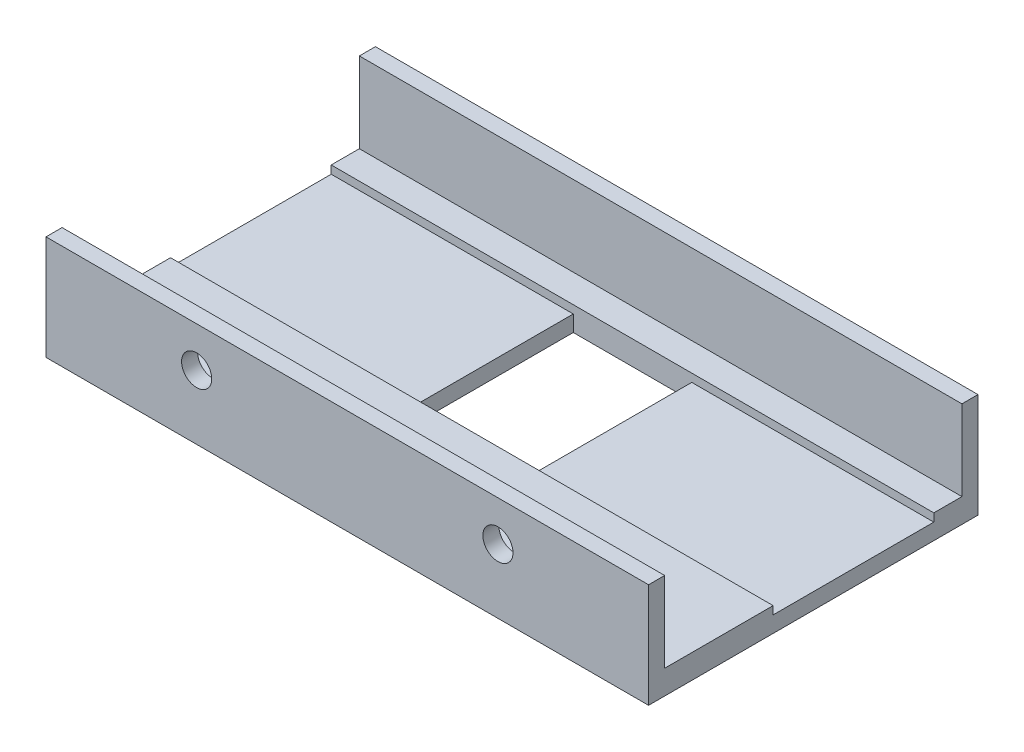
SolidWorks part; units mm, degrees
material "1345 Alloy"
ref_plane "Front Plane" through (0, 0, 0) normal (0, 0, 1) x (1, 0, 0)
ref_plane "Top Plane" through (0, 0, 0) normal (0, 1, 0) x (1, 0, 0)
ref_plane "Right Plane" through (0, 0, 0) normal (1, 0, 0) x (0, 0, -1)
sketch "Sketch1" plane through (0, 0, 0) normal (0, 1, 0) x (1, 0, 0)
  line L1 (-37.5, 20.5) -> (37.5, 20.5)
  line L2 (-37.5, 20.5) -> (-37.5, -20.5)
  line L3 (-37.5, -20.5) -> (37.5, -20.5)
  line L4 (37.5, 20.5) -> (37.5, -20.5)
  line L5 (-37.5, 20.5) -> (37.5, -20.5) construction
  line L6 (-37.5, -20.5) -> (37.5, 20.5) construction
  point P0 (0, 0)
  dimension "D1" = 41
  dimension "D2" = 75
extrude "Boss-Extrude1" add sketch "Sketch1" along normal blind 3
sketch "Sketch2" plane through (0, 3, 0) normal (0, 1, 0) x (1, 0, 0)
  line L0 (37.5, -20.5) -> (37.5, 20.5) construction
  line L1 (-37.5, 20.5) -> (37.5, 20.5)
  line L2 (-37.5, 20.5) -> (-37.5, 18.5)
  line L3 (-37.5, 18.5) -> (37.5, 18.5)
  line L4 (37.5, 20.5) -> (37.5, 18.5)
  dimension "D1" = 2
extrude "Boss-Extrude2" add sketch "Sketch2" along normal blind 10
sketch "Sketch3" plane through (0, 3, 0) normal (0, 1, 0) x (1, 0, 0)
  line L0 (37.5, -20.5) -> (37.5, 18.5) construction
  line L1 (-37.5, -20.5) -> (37.5, -20.5)
  line L2 (-37.5, -20.5) -> (-37.5, -18.5)
  line L3 (-37.5, -18.5) -> (37.5, -18.5)
  line L4 (37.5, -20.5) -> (37.5, -18.5)
  dimension "D1" = 2
extrude "Boss-Extrude3" add sketch "Sketch3" along normal up to surface (10 mm away) up to face at (0, 13, -19.5)
sketch "Sketch4" plane through (0, 0, 20.5) normal (0, 0, 1) x (1, 0, 0)
  line L4 (0, 0) -> (0, 13) construction
  line L5 (-37.5, 0) -> (37.5, 0) construction
  line L6 (-37.5, 13) -> (37.5, 13) construction
  line L8 (-39.5, -2) -> (39.5, -2)
  line L9 (39.5, -2) -> (39.5, 15)
  line L10 (39.5, 15) -> (-39.5, 15)
  line L11 (-39.5, 15) -> (-39.5, -2)
  line L12 (-39.5, -2) -> (39.5, -2)
  line L13 (39.5, -2) -> (39.5, 15)
  line L14 (39.5, 15) -> (-39.5, 15)
  line L15 (-39.5, 15) -> (-39.5, -2)
  circle A1 centre (18.75, 8) radius 1.875
  circle A2 centre (-18.75, 8) radius 1.875
  circle A3 centre (-18.75, 8) radius 1.875
  dimension "D1" = 2
  dimension "D2" = 0.5
extrude "Cut-Extrude2" cut sketch "Sketch4" against normal up to surface (2 mm away) flip side to cut up to face at (0, 8, 18.5)
sketch "Sketch6" plane through (0, 3, 0) normal (0, 1, 0) x (1, 0, 0)
  line L0 (-37.5, 18.5) -> (-37.5, -8.5) construction
  line L1 (-37.5, 18.5) -> (-37.5, -18.5) construction
  line L2 (-37.5, -8.5) -> (37.5, -8.5) construction
  line L3 (37.5, -18.5) -> (37.5, 18.5) construction
  line L4 (37.5, -8.5) -> (37.5, 18.5) construction
  line L5 (37.5, 18.5) -> (-37.5, 18.5) construction
  line L6 (-22.9033, -8.5) -> (22.0967, -8.5) construction
  line L7 (-37.5, 5) -> (37.5, 5) construction
  line L8 (0, 18.5) -> (0, -8.5) construction
  line L10 (-7.375, 15) -> (7.375, 15)
  line L11 (-7.375, 15) -> (-7.375, -5)
  line L12 (-7.375, -5) -> (7.375, -5)
  line L13 (7.375, 15) -> (7.375, -5)
  line L14 (-7.375, 15) -> (7.375, -5) construction
  line L15 (-7.375, -5) -> (7.375, 15) construction
  point P17 (0, 5)
  dimension "D1" = 14.75
  dimension "D2" = 20
  dimension "D3" = 3.5
extrude "Cut-Extrude3" cut sketch "Sketch6" against normal through all
sketch "Sketch7" plane through (0, 3, 0) normal (0, 1, 0) x (1, 0, 0)
  line L0 (-37.5, 18.5) -> (-37.5, -18.5) construction
  line L1 (-37.5, 15) -> (37.5, 15)
  line L2 (-37.5, 15) -> (-37.5, -5)
  line L3 (-37.5, -5) -> (37.5, -5)
  line L4 (37.5, 15) -> (37.5, -5)
  line L5 (37.5, -18.5) -> (37.5, 18.5) construction
  line L6 (7.375, 15) -> (-7.375, 15) construction
  line L7 (-7.375, -5) -> (7.375, -5) construction
extrude "Cut-Extrude4" cut sketch "Sketch7" against normal blind 1
